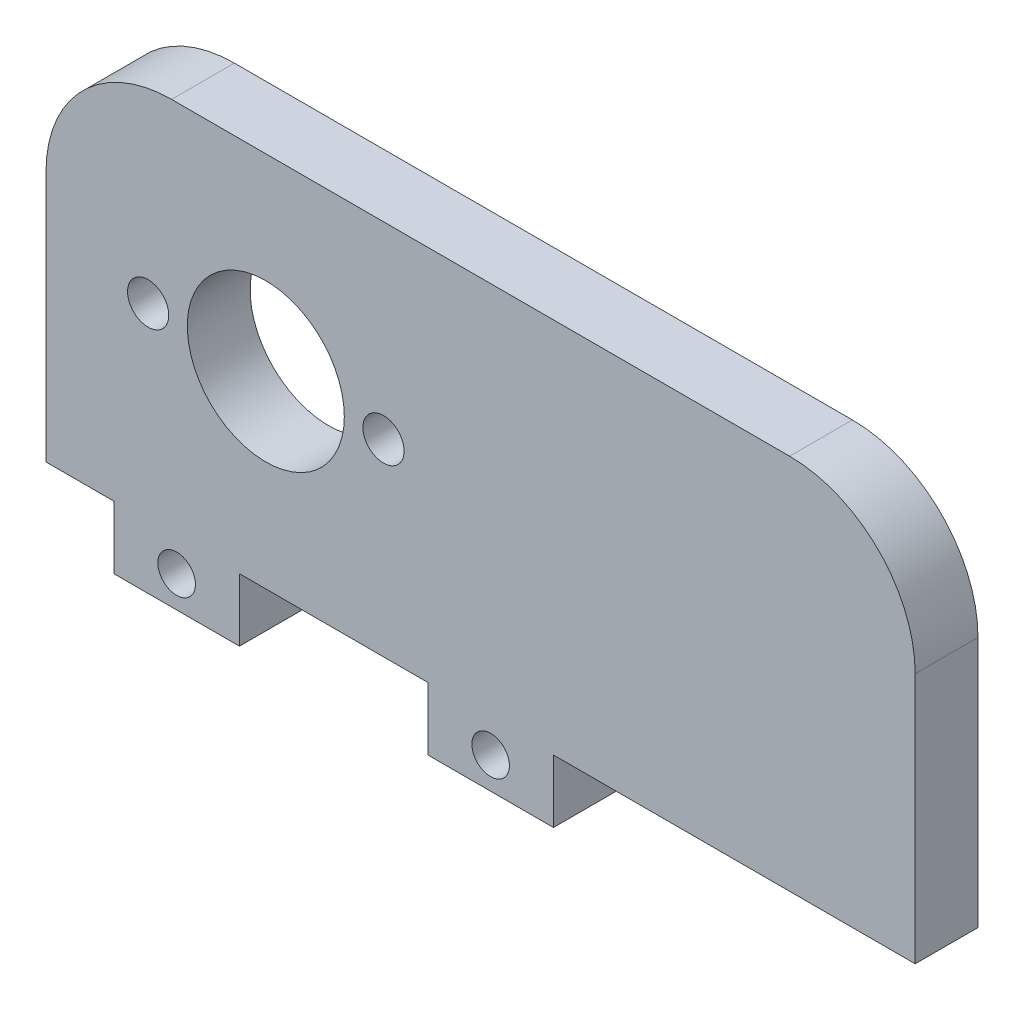
SolidWorks part; units mm, degrees
material "Beech"
ref_plane "Front Plane" through (0, 0, 0) normal (0, 0, 1) x (1, 0, 0)
ref_plane "Top Plane" through (0, 0, 0) normal (0, 1, 0) x (1, 0, 0)
ref_plane "Right Plane" through (0, 0, 0) normal (1, 0, 0) x (0, 0, -1)
sketch "Sketch2" plane through (0, 0, 0) normal (0, 0, 1) x (1, 0, 0)
  line L1 (-43.942, 22.225) -> (43.942, 22.225)
  line L2 (-43.942, 22.225) -> (-43.942, -22.225)
  line L3 (-43.942, -22.225) -> (43.942, -22.225)
  line L4 (43.942, 22.225) -> (43.942, -22.225)
  line L5 (-43.942, 22.225) -> (43.942, -22.225) construction
  line L6 (-43.942, -22.225) -> (43.942, 22.225) construction
  point P0 (0, 0)
  dimension "D1" = 44.45
  dimension "D2" = 87.884
extrude "Boss-Extrude1" add sketch "Sketch2" along normal mid plane 6.35
sketch "Sketch3" plane through (0, 0, 3.175) normal (0, 0, 1) x (1, 0, 0)
  line L2 (-43.942, 22.225) -> (-43.942, -22.225) construction
  line L3 (-43.942, -22.225) -> (43.942, -22.225) construction
  circle A0 centre (-21.717, 3.175) radius 7.9375
  dimension "D3" = 15.875
  dimension "D1" = 25.4
  dimension "D2" = 22.225
extrude "Cut-Extrude1" cut sketch "Sketch3" against normal up to next
hole_wizard "#8 Clearance Hole1" positions "Sketch5" profile "Sketch4" hole size "#8" standard "ANSI Inch" end condition up to next
sketch "Sketch5" plane through (0, 0, 3.175) normal (0, 0, 1) x (1, 0, 0)
  line L0 (-21.717, 3.175) -> (-33.6169, 3.175) construction
  point P2 (-33.6169, 3.175)
  dimension "D1" = 11.8999
sketch "Sketch4" plane through (-33.6169, 3.175, 3.175) normal (1, 0, 0) x (0, -1, 0)
  line L0 (0, 0) -> (0, 6.351)
  line L1 (0, 6.351) -> (2.0828, 6.351)
  line L2 (2.0828, 6.351) -> (2.0828, 0)
  line L5 (2.0828, 0) -> (0, 0)
  line L11 (0, -6.35) -> (0, 107.95) construction
  dimension "Thru Hole Dia." = 4.1656
  dimension "Thru Hole Depth" = 6.351
pattern_circular "CirPattern1" count 2 over 360 about axis through (-21.717, 3.175, 0) along (0, 0, 1) of "#8 Clearance Hole1"
sketch "Sketch6" plane through (0, 0, 3.175) normal (0, 0, 1) x (1, 0, 0)
  line L0 (-43.942, 22.225) -> (-43.942, -22.225) construction
  line L1 (-43.942, -15.875) -> (-37.084, -15.875)
  line L2 (-43.942, -15.875) -> (-43.942, -22.225)
  line L3 (-43.942, -22.225) -> (-37.084, -22.225)
  line L4 (-37.084, -15.875) -> (-37.084, -22.225)
  line L5 (-43.942, -22.225) -> (43.942, -22.225) construction
  line L6 (43.942, -22.225) -> (43.942, 22.225) construction
  line L7 (-24.384, -15.875) -> (-5.334, -15.875)
  line L8 (-24.384, -15.875) -> (-24.384, -22.225)
  line L9 (-24.384, -22.225) -> (-5.334, -22.225)
  line L10 (-5.334, -15.875) -> (-5.334, -22.225)
  line L11 (7.366, -15.875) -> (43.942, -15.875)
  line L12 (7.366, -15.875) -> (7.366, -22.225)
  line L13 (7.366, -22.225) -> (43.942, -22.225)
  line L14 (43.942, -15.875) -> (43.942, -22.225)
  dimension "D1" = 6.35
  dimension "D2" = 12.7
  dimension "D3" = 12.7
  dimension "D4" = 6.858
  dimension "D5" = 19.05
extrude "Cut-Extrude2" cut sketch "Sketch6" against normal up to next
hole_wizard "#6 Clearance Hole1" positions "Sketch8" profile "Sketch7" hole size "#6" standard "ANSI Inch"
sketch "Sketch8" plane through (0, 0, 3.175) normal (0, 0, 1) x (1, 0, 0)
  line L8 (-5.334, -15.875) -> (7.366, -22.225) construction
  line L9 (-5.334, -15.875) -> (-24.384, -15.875) construction
  line L10 (-5.334, -22.225) -> (-5.334, -15.875) construction
  line L12 (-37.084, -15.875) -> (-24.384, -22.225) construction
  point P81 (-30.734, -19.05)
  point P83 (1.016, -19.05)
sketch "Sketch7" plane through (1.016, -19.05, 3.175) normal (1, 0, 0) x (0, -1, 0)
  line L0 (0, 0) -> (0, 7.4908)
  line L1 (0, 7.4908) -> (1.8986, 6.35)
  line L2 (1.8986, 6.35) -> (1.8986, 0)
  line L5 (1.8986, 0) -> (0, 0)
  line L10 (0, 7.4908) -> (-1.8986, 6.35) construction
  line L11 (0, -6.35) -> (0, 107.95) construction
  dimension "Hole Dia." = 3.7973
  dimension "Hole Depth" = 6.35
  dimension "Drill Angle" = 118
ref_plane "Plane1" through (0, -19.05, 0) normal (0, -1, 0) x (-1, 0, 0)
fillet "Fillet1" radius 12.7 2 edges at (43.942, 22.225, 0) (-43.942, 22.225, 0)
